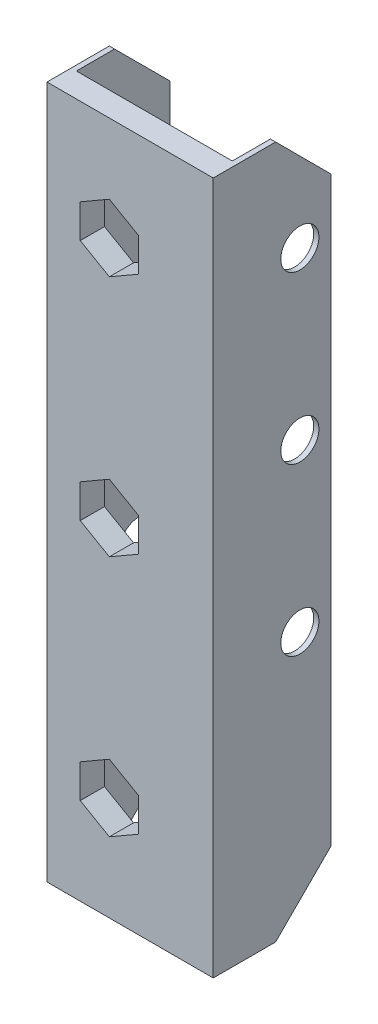
SolidWorks part; units mm, degrees
ref_plane "Front" through (0, 0, 0) normal (0, 0, 1) x (1, 0, 0)
ref_plane "Top" through (0, 0, 0) normal (0, 1, 0) x (1, 0, 0)
ref_plane "Right" through (0, 0, 0) normal (1, 0, 0) x (0, 0, -1)
sketch "Sketch1" plane through (0, 0, 0) normal (0, 1, 0) x (1, 0, 0)
  line L0 (0, 0) -> (0, 17)
  line L1 (0, 17) -> (0.75, 17)
  line L2 (0.75, 17) -> (0.75, 3.5)
  line L3 (0.75, 3.5) -> (23.25, 3.5)
  line L4 (23.25, 3.5) -> (23.25, 17)
  line L5 (23.25, 17) -> (24, 17)
  line L6 (24, 17) -> (24, 0)
  line L7 (24, 0) -> (0, 0)
  dimension "D1" = 3.5
  dimension "D2" = 0.75
  dimension "D3" = 24
  dimension "D4" = 17
extrude "Boss-Extrude1" add sketch "Sketch1" along normal blind 100 contours L3 L4 L5 L6 L7 L0 L1 L2
sketch "Sketch2" plane through (0, 0, 0) normal (0, 0, 1) x (1, 0, 0)
  line L0 (24, 100) -> (0, 100) construction
  line L1 (9, 80.1503) -> (13.2, 82.5751)
  line L2 (13.2, 82.5751) -> (13.2, 87.4249)
  line L3 (13.2, 87.4249) -> (9, 89.8497)
  line L4 (9, 89.8497) -> (4.8, 87.4249)
  line L5 (4.8, 87.4249) -> (4.8, 82.5751)
  line L6 (4.8, 82.5751) -> (9, 80.1503)
  line L7 (9, 45.1503) -> (13.2, 47.5751)
  line L8 (13.2, 47.5751) -> (13.2, 52.4249)
  line L9 (13.2, 52.4249) -> (9, 54.8497)
  line L10 (9, 54.8497) -> (4.8, 52.4249)
  line L11 (4.8, 52.4249) -> (4.8, 47.5751)
  line L12 (4.8, 47.5751) -> (9, 45.1503)
  line L13 (9, 19.8497) -> (4.8, 17.4249)
  line L14 (4.8, 17.4249) -> (4.8, 12.5751)
  line L15 (4.8, 12.5751) -> (9, 10.1503)
  line L16 (9, 10.1503) -> (13.2, 12.5751)
  line L17 (13.2, 12.5751) -> (13.2, 17.4249)
  line L18 (13.2, 17.4249) -> (9, 19.8497)
  line L20 (0, 100) -> (0, 0) construction
  circle A0 centre (9, 85) radius 4.2 construction
  circle A1 centre (9, 50) radius 4.2 construction
  circle A2 centre (9, 15) radius 4.2 construction
  dimension "D1" = 35
  dimension "D2" = 35
  dimension "D3" = 15
  dimension "D4" = 8.4
  dimension "D5" = 9
extrude "Cut-Extrude1" cut sketch "Sketch2" against normal through all both and the other way through all contours L11 L12 L7 L8 L9 L10 | L17 L18 L13 L14 L15 L16 | L5 L6 L1 L2 L3 L4
hole_wizard "M5 Clearance Hole1" positions "Sketch3" profile "Sketch4" hole size "M5" standard "ISO" end condition through all
sketch "Sketch3" plane through (24, 0, 0) normal (1, 0, 0) x (0, 0, -1)
  line L0 (17, 100) -> (0, 100) construction
  line L2 (3.5, 100) -> (3.5, 0) construction
  point P0 (12.5, 85)
  point P2 (12.5, 37)
  point P4 (12.5, 61)
  dimension "D1" = 24
  dimension "D2" = 24
  dimension "D3" = 15
  dimension "D4" = 9
sketch "Sketch4" plane through (24, 85, -12.5) normal (0, 1, 0) x (0, 0, -1)
  line L0 (0, 0) -> (0, 24)
  line L1 (0, 24) -> (2.75, 24)
  line L2 (2.75, 24) -> (2.75, 0)
  line L5 (2.75, 0) -> (0, 0)
  line L11 (0, -6.35) -> (0, 107.95) construction
  dimension "Thru Hole Dia." = 5.5
  dimension "Thru Hole Depth" = 24
chamfer "Chamfer1" distance 8 angle 45 4 edges at (0.375, 100, -17) (23.625, 100, -17) (23.625, 0, -17) (0.375, 0, -17)
